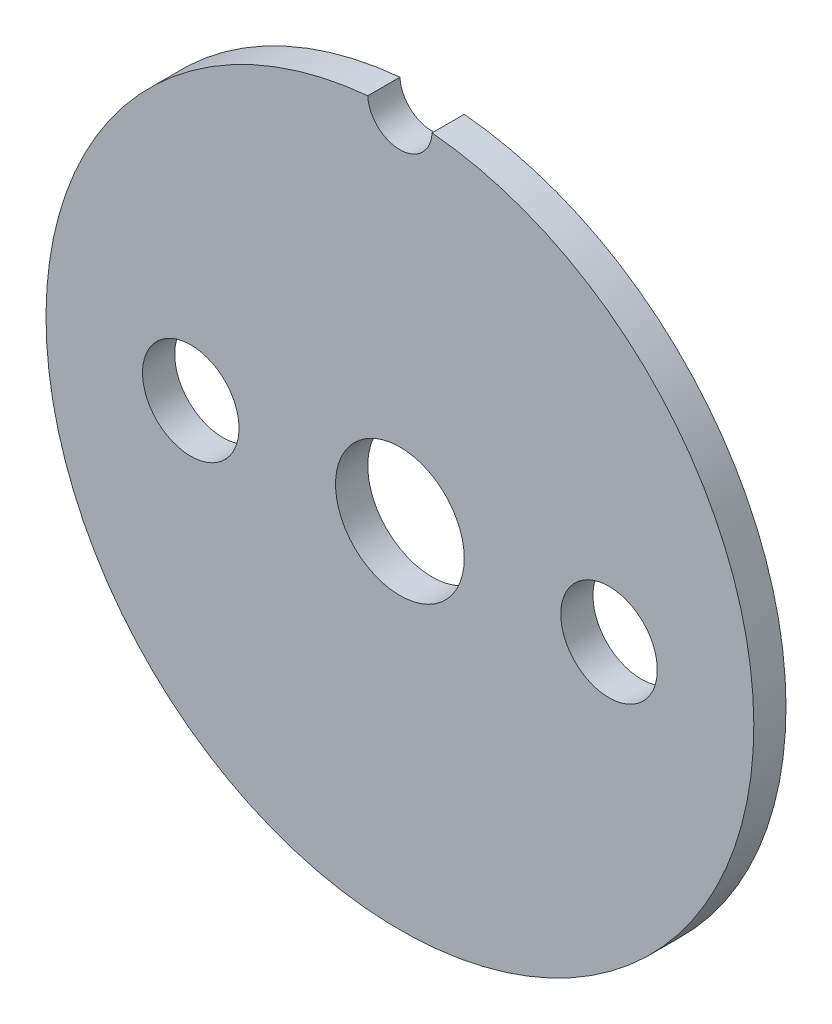
SolidWorks part; units mm, degrees
ref_plane "前视基准面" through (0, 0, 0) normal (0, 0, 1) x (1, 0, 0)
ref_plane "上视基准面" through (0, 0, 0) normal (0, 1, 0) x (1, 0, 0)
ref_plane "右视基准面" through (0, 0, 0) normal (1, 0, 0) x (0, 0, -1)
sketch "草图1" plane through (0, 0, 0) normal (0, 0, 1) x (1, 0, 0)
  line L0 (0.7836, -0.3918) -> (0.7836, -3.8918) construction
  line L1 (0.7836, -3.8918) -> (-5.7164, -3.8918) construction
  circle A0 centre (-5.7164, -3.8918) radius 1.5
  circle A1 centre (7.2836, -3.8918) radius 1.5
  circle A2 centre (0.7836, -3.8918) radius 2
  circle A4 centre (0.7836, -3.8918) radius 11
  dimension "D1" = 3.5
  dimension "D2" = 6.5
extrude "凸台-拉伸1" add sketch "草图1" along normal blind 1
sketch "草图2" plane through (0, 0, 1) normal (0, 0, 1) x (1, 0, 0)
  circle A0 centre (0.7836, 7.1082) radius 1
  circle A1 centre (0.7836, -3.8918) radius 11 construction
extrude "切除-拉伸1" cut sketch "草图2" against normal blind 10
